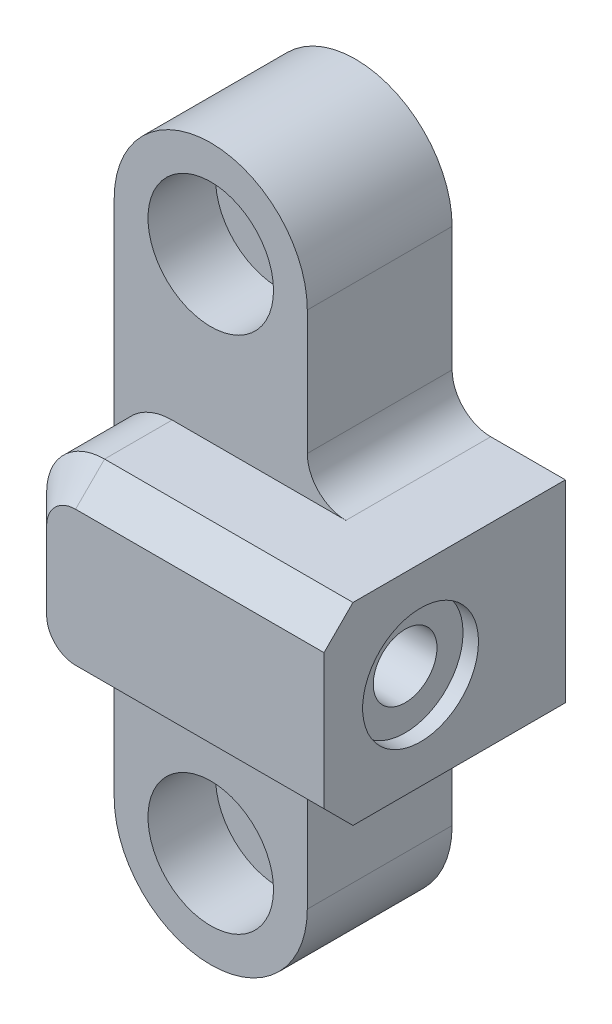
SolidWorks part; units mm, degrees
ref_plane "前视基准面" through (0, 0, 0) normal (0, 0, 1) x (1, 0, 0)
ref_plane "上视基准面" through (0, 0, 0) normal (0, 1, 0) x (1, 0, 0)
ref_plane "右视基准面" through (0, 0, 0) normal (1, 0, 0) x (0, 0, -1)
ref_plane "基准面1" through (0, 5, 0) normal (0, 1, 0) x (1, 0, 0)
sketch "草图1" plane through (0, 5, 0) normal (0, 1, 0) x (1, 0, 0)
  line L0 (24.3, 0) -> (8.435, 0)
  line L1 (8.435, 0) -> (8.435, -12.5)
  line L2 (8.435, -12.5) -> (24.3, -12.5)
  line L3 (24.3, -12.5) -> (24.3, 0)
extrude "凸台-拉伸1" add sketch "草图1" against normal blind 10
ref_plane "基准面2" through (0, 0, 0) normal (0, 0, -1) x (-1, 0, 0)
sketch "草图2" plane through (0, 0, 0) normal (0, 0, -1) x (-1, 0, 0)
  line L0 (-8.435, -5) -> (-18.435, -5)
  line L1 (-18.435, -5) -> (-18.435, -13.435)
  line L2 (-8.435, -13.435) -> (-8.435, -5)
  arc A0 (-18.435, -13.435) -> (-8.435, -13.435) centre (-13.435, -13.435) ccw
extrude "凸台-拉伸2" add sketch "草图2" against normal blind 7.5
sketch "草图3" plane through (0, 0, 0) normal (0, 0, -1) x (-1, 0, 0)
  line L0 (-8.435, 5) -> (-8.435, 13.435)
  line L1 (-18.435, 13.435) -> (-18.435, 5)
  line L2 (-18.435, 5) -> (-8.435, 5)
  arc A0 (-8.435, 13.435) -> (-18.435, 13.435) centre (-13.435, 13.435) ccw
extrude "凸台-拉伸3" add sketch "草图3" against normal blind 7.5
hole_wizard "M3 六角头机械螺钉的柱形沉头孔1" positions "草图5" profile "草图4" counterbore size "M3" standard "ANSI Metric"
sketch "草图5" plane through (24.3, 0, 0) normal (1, 0, 0) x (0, 0, -1)
  point P0 (-7.5, 0)
sketch "草图4" plane through (24.3, 0, 7.5) normal (0, 1, 0) x (0, 0, -1)
  line L0 (0, 0) -> (0, 10.7914)
  line L1 (0, 10.7914) -> (1.65, 9.8)
  line L2 (1.65, 9.8) -> (1.65, 0.8)
  line L3 (1.65, 0.8) -> (3, 0.8)
  line L4 (3, 0.8) -> (3, 0)
  line L5 (3, 0) -> (0, 0)
  line L10 (0, 10.7914) -> (-1.65, 9.8) construction
  line L11 (0, -6.35) -> (0, 107.95) construction
  dimension "孔直径" = 3.3
  dimension "孔深度" = 9.8
  dimension "柱形沉头孔直径" = 6
  dimension "柱形沉头孔深度" = 0.8
  dimension "导头角度" = 118
hole_wizard "M3 六角头机械螺钉的柱形沉头孔2" positions "草图7" profile "草图6" counterbore size "M3" standard "ANSI Metric"
sketch "草图7" plane through (0, 0, 7.5) normal (0, 0, 1) x (1, 0, 0)
  point P0 (13.435, 13.435)
  point P1 (13.435, -13.435)
sketch "草图6" plane through (13.435, 13.435, 7.5) normal (1, 0, 0) x (0, -1, 0)
  line L0 (0, 0) -> (0, 7.5)
  line L1 (0, 7.5) -> (1.7, 7.5)
  line L3 (1.7, 7.5) -> (1.7, 3.5)
  line L4 (1.7, 3.5) -> (3.25, 3.5)
  line L5 (3.25, 3.5) -> (3.25, 0)
  line L7 (3.25, 0) -> (0, 0)
  line L11 (0, -6.35) -> (0, 107.95) construction
  dimension "通孔孔直径" = 3.4
  dimension "通孔孔深度" = 7.5
  dimension "柱形沉头孔直径" = 6.5
  dimension "柱形沉头孔深度" = 3.5
fillet "圆角1" radius 3 2 edges at (8.435, -5, 10) (8.435, 5, 10)
chamfer "倒角1" distance 1.5 angle 45 5 edges at (17.8675, 5, 12.5) (9.3137, 4.1213, 12.5) (8.435, 0, 12.5) (9.3137, -4.1213, 12.5) (17.8675, -5, 12.5)
fillet "圆角2" radius 2 2 edges at (18.435, 5, 3.75) (18.435, -5, 3.75)
